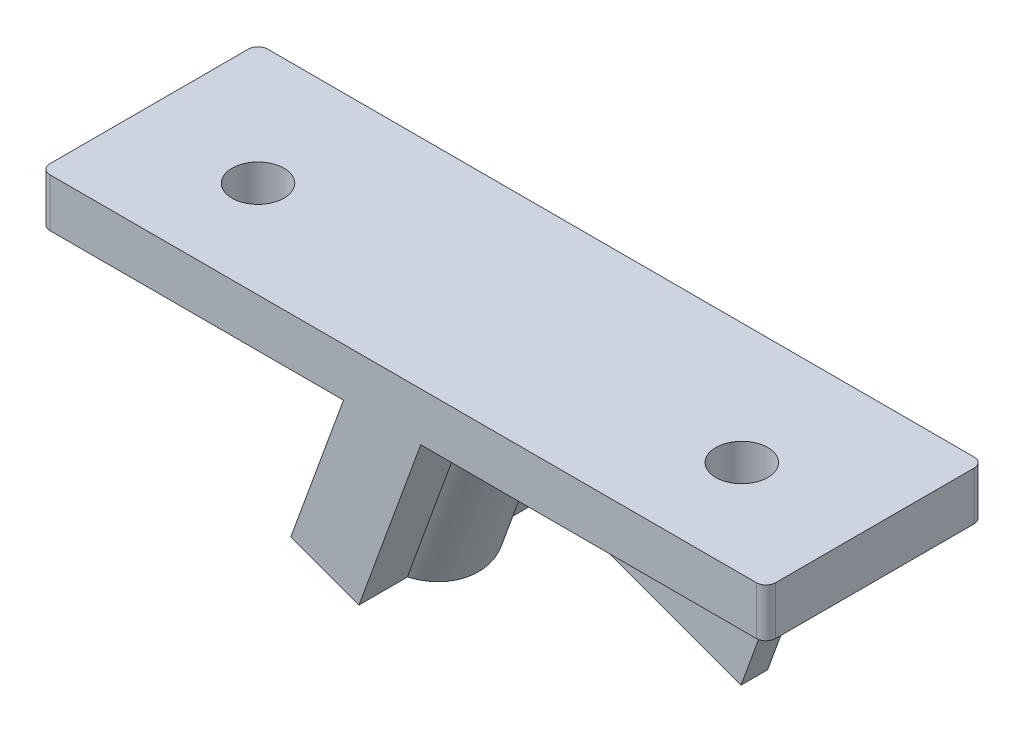
SolidWorks part; units mm, degrees
ref_plane "前视基准面" through (0, 0, 0) normal (0, 0, 1) x (1, 0, 0)
ref_plane "上视基准面" through (0, 0, 0) normal (0, 1, 0) x (1, 0, 0)
ref_plane "右视基准面" through (0, 0, 0) normal (1, 0, 0) x (0, 0, -1)
other "Configuration Table"
sketch "草图1" plane through (0, 0, 0) normal (0, 1, 0) x (1, 0, 0)
  line L1 (-30, 18) -> (30, 18)
  line L2 (-30, 18) -> (-30, 0)
  line L3 (-30, 0) -> (30, 0)
  line L4 (30, 18) -> (30, 0)
  line L5 (-30, 18) -> (30, 0) construction
  line L6 (-30, 0) -> (30, 18) construction
  circle A0 centre (-20, 8) radius 2.15
  circle A1 centre (20, 8) radius 2.15
  point P4 (0, 9)
  dimension "D3" = 4.3
  dimension "D4" = 4.3
  dimension "D1" = 60
  dimension "D2" = 18
  dimension "D5" = 20
  dimension "D6" = 8
  dimension "D7" = 8
  dimension "D8" = 20
extrude "凸台-拉伸1" add sketch "草图1" along normal blind 4
ref_plane "基准面1" through (0, -23, 0) normal (0, -1, 0) x (-1, 0, 0)
sketch "草图2" plane through (0, -23, 0) normal (0, -1, 0) x (-1, 0, 0)
  point P0 (0, 0)
sketch "草图3" plane through (0, 0, 0) normal (0, -1, 0) x (1, 0, 0)
  line L0 (4, 0) -> (4, -18) construction
  dimension "D1" = 4
ref_plane "基准面2" through (0.4679, 1.2856, 0) normal (0.342, 0.9397, 0) x (0, 0, -1)
sketch "草图5" plane through (0, 0, -18) normal (0, 0, -1) x (-1, 0, 0)
  line L0 (-19.3323, 0) -> (10.039, 0)
  line L1 (-30, 0) -> (30, 0) construction
  line L3 (-19.3323, 0) -> (-12.1343, -19.7764)
  line L4 (10.039, 0) -> (13.8012, -10.3366)
  line L5 (-12.1343, -19.7764) -> (13.8012, -10.3366)
  dimension "D1" = 10.3
  dimension "D2" = 17.3
  dimension "D3" = 11
extrude "凸台-拉伸3" add sketch "草图5" against normal blind 2.2
sketch "草图4" plane through (0.4679, 1.2856, 0) normal (0.342, 0.9397, 0) x (0, 0, -1)
  line L0 (0, 29.5589) -> (0, -26.8227) construction
  line L1 (0, 4.6335) -> (4, 4.6335)
  line L2 (18, -26.8227) -> (18, 29.5589) construction
  line L3 (0, -1.3665) -> (4, -1.3665)
  line L4 (0, 4.6335) -> (0, -1.3665)
  line L5 (18, 4.6335) -> (18, -1.3665)
  line L6 (12, 4.6335) -> (18, 4.6335)
  line L7 (12, -1.3665) -> (18, -1.3665)
  arc A0 (4, -1.3665) -> (12, -1.3665) centre (8, 1.6335) ccw
  arc A1 (12, 4.6335) -> (4, 4.6335) centre (8, 1.6335) ccw
  dimension "D1" = 10
  dimension "D2" = 9.5
  dimension "D3" = 8
  dimension "D4" = 3
  dimension "D5" = 3
sketch "草图6" plane through (0, 0, -18) normal (0, 0, -1) x (-1, 0, 0)
  line L0 (-16.3652, -8.7371) -> (-9.8668, -26.5912)
  line L1 (0, 0) -> (35.5322, 0) construction
  line L2 (16.4446, -17.0146) -> (-9.8668, -26.5912)
  line L3 (9.9462, 0.8395) -> (16.4446, -17.0146)
  line L4 (-16.3652, -8.7371) -> (9.9462, 0.8395)
  dimension "D1" = 17.5
  dimension "D2" = 19
  dimension "D3" = 10.5
  dimension "D4" = 20
fillet "圆角1" radius 0.8 4 edges at (-30, 2, -18) (-30, 2, 0) (30, 2, 0) (30, 2, -18)
extrude "凸台-拉伸4" add sketch "草图4" against normal up to surface (15.8016 mm away) up to face at (-0.8334, -15.0565, -16.9)
